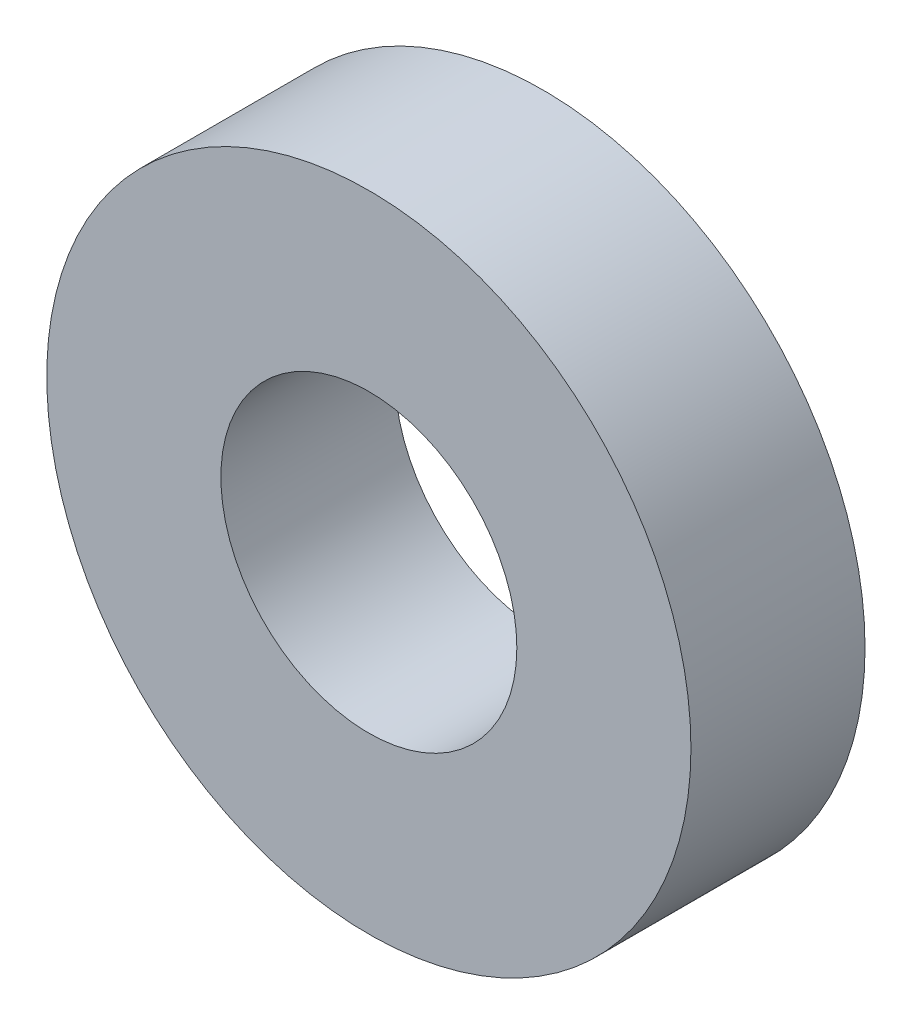
SolidWorks part; units mm, degrees
ref_plane "Front Plane" through (0, 0, 0) normal (0, 0, 1) x (1, 0, 0)
ref_plane "Top Plane" through (0, 0, 0) normal (0, 1, 0) x (1, 0, 0)
ref_plane "Right Plane" through (0, 0, 0) normal (1, 0, 0) x (0, 0, -1)
sketch "Sketch1" plane through (0, 0, 0) normal (0, 0, 1) x (1, 0, 0)
  circle A1 centre (0, 0) radius 18.5
  circle A2 centre (0, 0) radius 8.5
  dimension "D1" = 37
  dimension "D2" = 17
extrude "Boss-Extrude1" add sketch "Sketch1" along normal blind 10 contours A1
